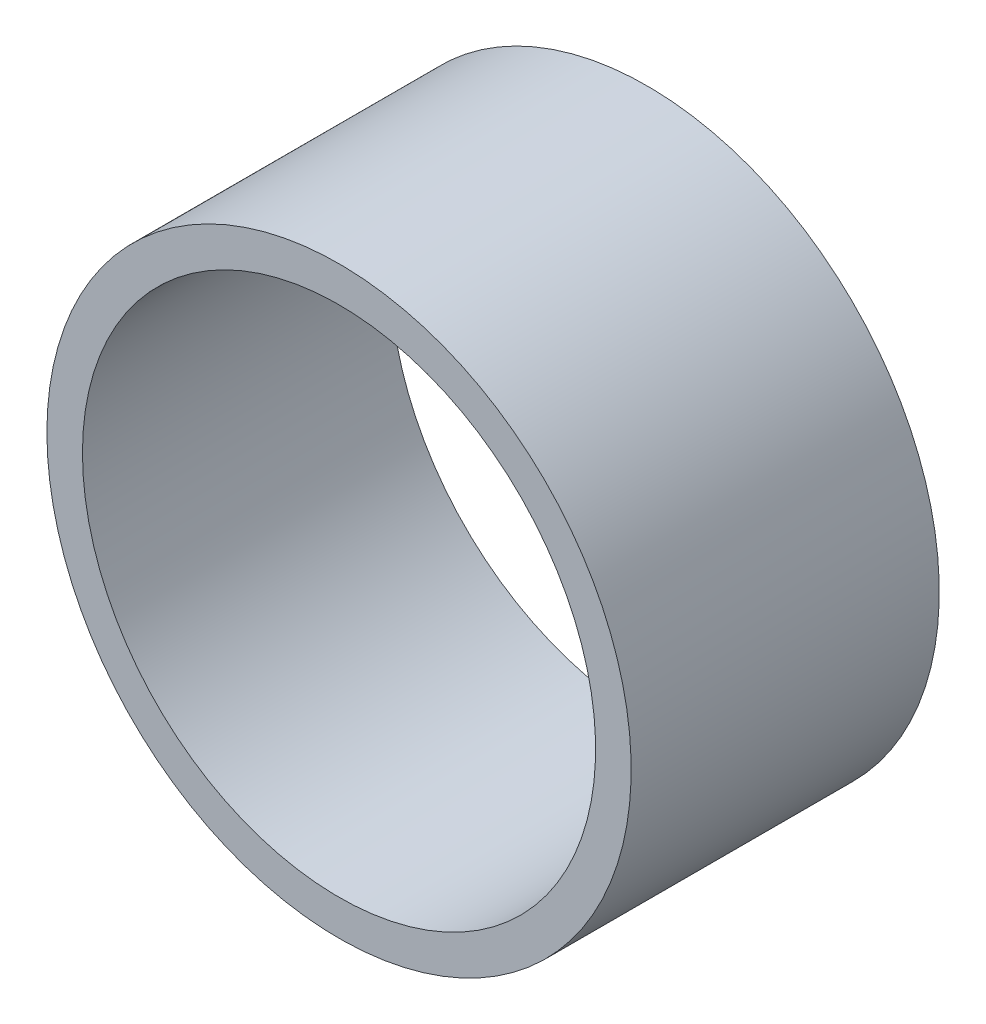
SolidWorks part; units mm, degrees
material "TPU 95A"
ref_plane "Front Plane" through (0, 0, 0) normal (1, 0, 0) x (0, 1, 0)
ref_plane "Top Plane" through (0, 0, 0) normal (0, 0, 1) x (0, 1, 0)
ref_plane "Right Plane" through (0, 0, 0) normal (0, 1, 0) x (-1, 0, 0)
sketch "Sketch1" plane through (0, 0, 0) normal (0, 0, 1) x (0, 1, 0)
  circle A0 centre (0, 0) radius 5.5
  circle A1 centre (0, 0) radius 6.262
  dimension "D1" = 11
  dimension "D2" = 12.524
extrude "Boss-Extrude1" add sketch "Sketch1" along normal blind 6.604
equation "\"D2@Sketch1\"=11mm+0.06in"
